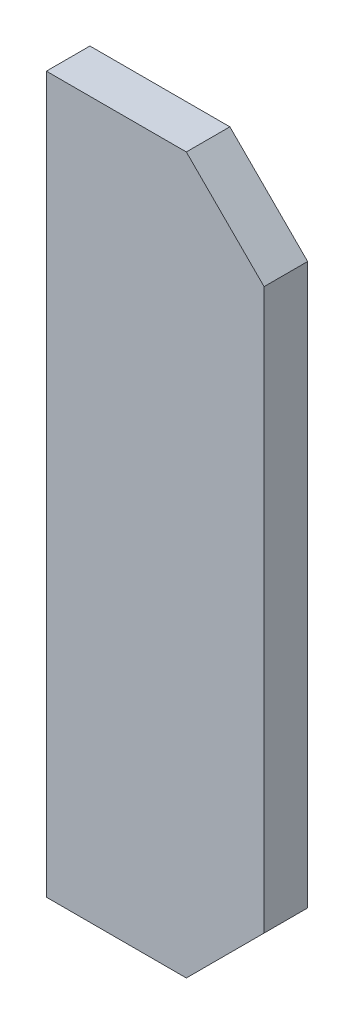
SolidWorks part; units mm, degrees
ref_plane "前视" through (0, 0, 0) normal (0, 0, 1) x (1, 0, 0)
ref_plane "上视" through (0, 0, 0) normal (0, 1, 0) x (1, 0, 0)
ref_plane "右视" through (0, 0, 0) normal (1, 0, 0) x (0, 0, -1)
sketch "草图1" plane through (0, 0, 0) normal (0, 0, 1) x (1, 0, 0)
  line L0 (35, 276.754) -> (35, -116.5623) construction
  line L1 (0, 0) -> (45, 0)
  line L2 (0, 0) -> (0, 230)
  line L3 (0, 230) -> (45, 230)
  line L4 (70, 25) -> (70, 205)
  line L5 (45, 230) -> (70, 205)
  line L6 (35, 115) -> (151.4714, 115) construction
  line L7 (45, 0) -> (70, 25)
  dimension "D1" = 70
  dimension "D2" = 230
  dimension "D3" = 35
  dimension "D8" = 135
  dimension "D9" = 25
extrude "基体-拉伸" add sketch "草图1" along normal blind 14
